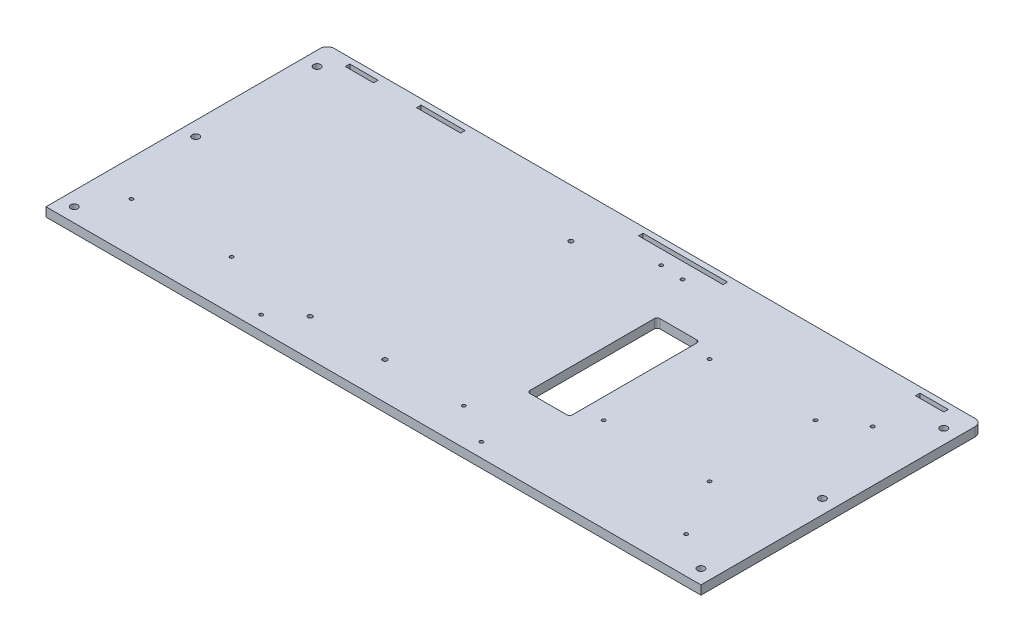
SolidWorks part; units mm, degrees
ref_plane "Front Plane" through (0, 0, 0) normal (0, 0, 1) x (1, 0, 0)
ref_plane "Top Plane" through (0, 0, 0) normal (0, 1, 0) x (1, 0, 0)
ref_plane "Right Plane" through (0, 0, 0) normal (1, 0, 0) x (0, 0, -1)
sketch "Sketch1" plane through (0, 0, 0) normal (0, 1, 0) x (1, 0, 0)
  line L1 (-20.2, 0) -> (443.68, 0)
  line L2 (-20.2, 0) -> (-20.2, -192)
  line L3 (-20.2, -192) -> (443.68, -192)
  line L4 (443.68, 0) -> (443.68, -192)
extrude "Boss-Extrude1" add sketch "Sketch1" against normal up to vertex (6.35 mm away)
sketch "Sketch5" plane through (0, 0, 0) normal (0, 1, 0) x (1, 0, 0)
  line L0 (-10.2, -10) -> (-10.2, -182) construction
  line L1 (433.68, -10) -> (433.68, -182) construction
  circle A0 centre (-10.2, -96) radius 2.5
  circle A1 centre (433.68, -96) radius 2.5
  circle A2 centre (-10.2, -10) radius 2.5
  circle A3 centre (-10.2, -182) radius 2.5
  circle A4 centre (433.68, -182) radius 2.5
  circle A5 centre (433.68, -10) radius 2.5
  point P15 (-10.2, -96)
  point P16 (433.68, -96)
  dimension "D2" = 5
  dimension "D1" = 10
extrude "Cut-Extrude3" cut sketch "Sketch5" against normal through all
sketch "Sketch4" plane through (0, 0, 0) normal (0, 1, 0) x (1, 0, 0)
  line L0 (-0.2, -182) -> (141.0933, -182) construction
  line L1 (-201107.5187, 0) -> (248892.4813, 0) construction
  line L2 (141.0933, -182) -> (282.3867, -182) construction
  circle A0 centre (407.33, -34.02) radius 1.25
  circle A1 centre (407.33, -166.1) radius 1.25
  circle A2 centre (249.85, -166.1) radius 1.25
  circle A3 centre (249.85, -11.16) radius 1.25
  circle A4 centre (186.8, -27.2) radius 1.6
  circle A5 centre (193.5, -165.7) radius 1.6
  circle A6 centre (140.6, -165.7) radius 1.6
  circle A7 centre (122.193, -182) radius 1.25
  circle A8 centre (278.193, -182) radius 1.25
  circle A9 centre (233.5, -10) radius 1.25
  circle A10 centre (5.25, -157) radius 1.25
  circle A11 centre (76.25, -157) radius 1.25
  circle A12 centre (308.24, -50.45) radius 1.25
  circle A13 centre (383.24, -50.45) radius 1.25
  circle A14 centre (383.24, -125.45) radius 1.25
  circle A15 centre (308.24, -125.45) radius 1.25
  dimension "D1" = 2.5
  dimension "D2" = 3.2
  dimension "D3" = 2.5
  dimension "D4" = 2.5
  dimension "D6" = 2.5
  dimension "D7" = 2.5
  dimension "D5" = 10
extrude "Cut-Extrude2" cut sketch "Sketch4" against normal through all
sketch "Sketch2" plane through (0, -6.35, 0) normal (0, -1, 0) x (1, 0, 0)
  line L0 (-201402.0628, -3.175) -> (248597.9372, -3.175) construction
  line L1 (-20.2, 0) -> (443.68, 0)
  line L2 (-20.2, 0) -> (-20.2, -7.175)
  line L3 (-20.2, -7.175) -> (443.68, -7.175)
  line L4 (443.68, 0) -> (443.68, -7.175)
  dimension "D1" = 4
extrude "Boss-Extrude2" add sketch "Sketch2" against normal up to surface (6.35 mm away) up to face at (278.193, 0, 183.25)
sketch "Sketch3" plane through (0, -6.35, 0) normal (0, -1, 0) x (1, 0, 0)
  line L32 (-202523.6313, 0) -> (323657.9361, 0) construction
  line L33 (-0.2, -3.175) -> (19.8, -3.175)
  line L34 (-0.2, -3.175) -> (-0.2, 0)
  line L35 (-0.2, 0) -> (19.8, 0)
  line L36 (19.8, -3.175) -> (19.8, 0)
  line L37 (9.8, 0) -> (9.8, -3.175) construction
  line L38 (-0.2, -1.5875) -> (19.8, -1.5875) construction
  line L39 (50.25, -3.175) -> (81.5, -3.175)
  line L40 (50.25, -3.175) -> (50.25, 0)
  line L41 (50.25, 0) -> (81.5, 0)
  line L42 (81.5, -3.175) -> (81.5, 0)
  line L43 (65.875, 0) -> (65.875, -3.175) construction
  line L44 (50.25, -1.5875) -> (81.5, -1.5875) construction
  line L45 (207.5, -3.175) -> (267.37, -3.175)
  line L46 (207.5, -3.175) -> (207.5, 0)
  line L47 (207.5, 0) -> (267.37, 0)
  line L48 (267.37, -3.175) -> (267.37, 0)
  line L49 (237.435, 0) -> (237.435, -3.175) construction
  line L50 (207.5, -1.5875) -> (267.37, -1.5875) construction
  line L51 (403.68, -3.175) -> (423.68, -3.175)
  line L52 (403.68, -3.175) -> (403.68, 0)
  line L53 (403.68, 0) -> (423.68, 0)
  line L54 (423.68, -3.175) -> (423.68, 0)
  line L55 (413.68, 0) -> (413.68, -3.175) construction
  line L56 (403.68, -1.5875) -> (423.68, -1.5875) construction
  line L57 (-201402.0628, -3.175) -> (248597.9372, -3.175) construction
  point P0 (9.8, -1.5875)
  point P4 (65.875, -1.5875)
  point P8 (237.435, -1.5875)
  point P12 (413.68, -1.5875)
extrude "Cut-Extrude1" cut sketch "Sketch3" against normal through all
fillet "Fillet1" radius 5 2 edges at (443.68, -3.175, -7.175) (-20.2, -3.175, -7.175)
sketch "Sketch6" plane through (0, 0, 0) normal (0, 1, 0) x (1, 0, 0)
  line L8 (263.85, -43.18) -> (263.85, -135.18)
  line L9 (263.85, -135.18) -> (293.85, -135.18)
  line L10 (293.85, -135.18) -> (293.85, -43.18)
  line L11 (293.85, -43.18) -> (263.85, -43.18)
  line L12 (263.85, -43.18) -> (263.85, -135.18)
  line L13 (263.85, -135.18) -> (293.85, -135.18)
  line L14 (293.85, -135.18) -> (293.85, -43.18)
  line L15 (293.85, -43.18) -> (263.85, -43.18)
  dimension "D1" = 1
extrude "Cut-Extrude4" cut sketch "Sketch6" against normal through all
fillet "Fillet2" radius 2 4 edges at (293.85, -3.175, 135.18) (263.85, -3.175, 135.18) (263.85, -3.175, 43.18) (293.85, -3.175, 43.18)
